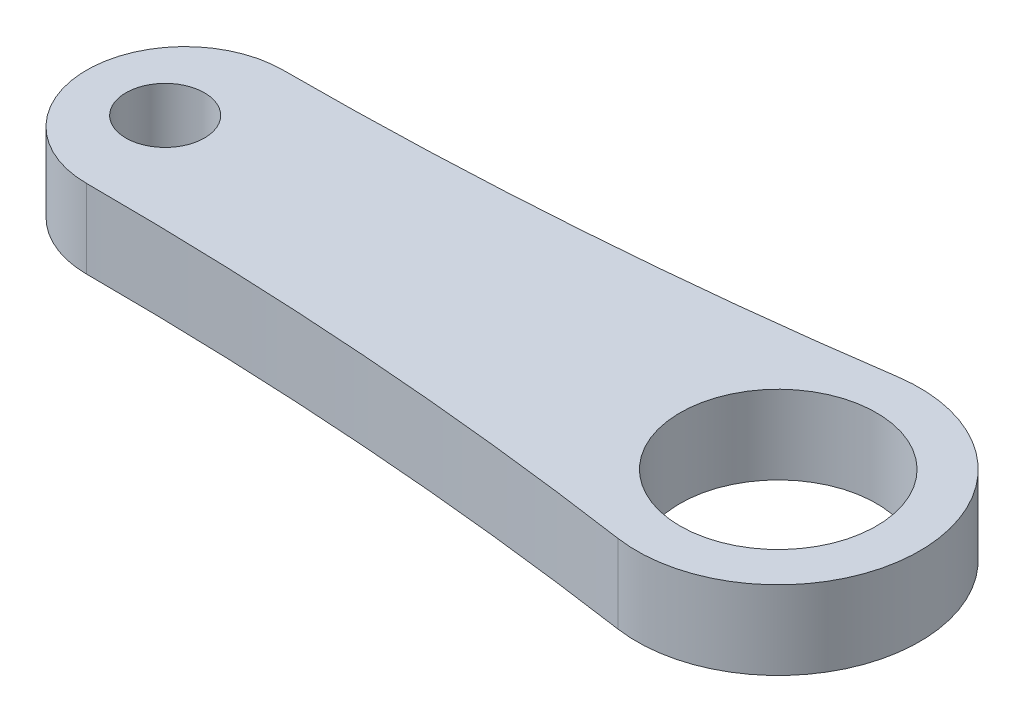
SolidWorks part; units mm, degrees
ref_plane "Alzado" through (0, 0, 0) normal (0, 0, 1) x (1, 0, 0)
ref_plane "Planta" through (0, 0, 0) normal (0, 1, 0) x (1, 0, 0)
ref_plane "Vista lateral" through (0, 0, 0) normal (1, 0, 0) x (0, 0, -1)
sketch "Croquis1" plane through (0, 44.4356, 0) normal (0, 1, 0) x (1, 0, 0)
  line L0 (-19.7658, -18.8449) -> (-19.2658, -18.8449) construction
  line L5 (-22.2658, -18.8449) -> (-20.2658, -18.8449) construction
  line L6 (-19.7658, -16.3449) -> (-7.2459, -16.3449)
  line L8 (-19.7658, -21.3449) -> (-7.2459, -21.3449)
  circle A0 centre (-4.6555, -18.8449) radius 2.5
  arc A1 (-7.2459, -21.3449) -> (-7.2459, -16.3449) centre (-4.6555, -18.8449) ccw
  arc A2 (-19.7658, -16.3449) -> (-19.7658, -21.3449) centre (-19.7658, -18.8449) ccw
  circle A5 centre (-20.2658, -18.8449) radius 1
  point P13 (0, 0)
  point P14 (0, 0)
  dimension "D1" = 5
  dimension "D2" = 7.2
  dimension "D4" = 5
  dimension "D5" = 2
  dimension "D3" = 2
extrude "Saliente-Extruir1" add sketch "Croquis1" along normal blind 2
fillet "Redondeo1" radius 101 2 edges at (-7.2459, 45.4356, 16.3449) (-7.2459, 45.4356, 21.3449)
